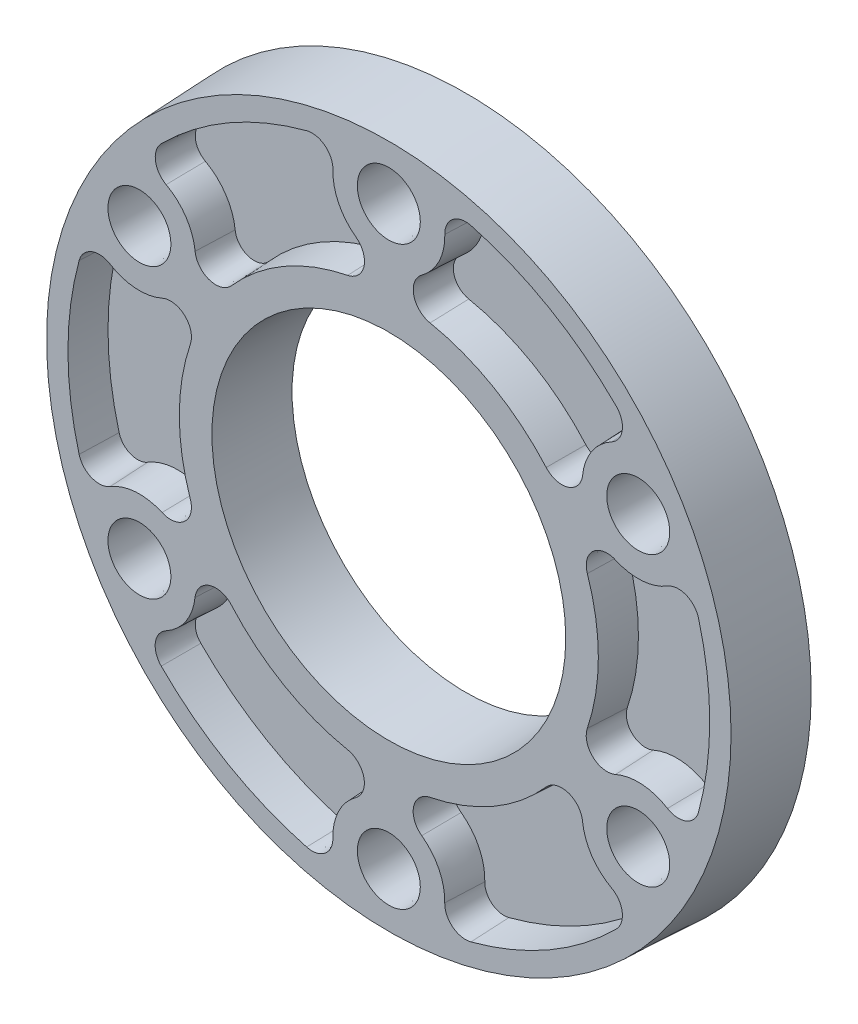
SolidWorks part; units mm, degrees
material "PUR"
ref_plane "Front Plane" through (0, 0, 0) normal (0, 0, 1) x (1, 0, 0)
ref_plane "Top Plane" through (0, 0, 0) normal (0, 1, 0) x (1, 0, 0)
ref_plane "Right Plane" through (0, 0, 0) normal (1, 0, 0) x (0, 0, -1)
sketch "Sketch1" plane through (0, 0, 0) normal (0, 1, 0) x (1, 0, 0)
  line L0 (28.575, 3.175) -> (0, 3.175)
  line L1 (0, 3.175) -> (0, -3.175)
  line L2 (0, -3.175) -> (28.2978, -3.175)
  line L3 (28.2978, -3.175) -> (28.575, 3.175)
  line L4 (0, 3.175) -> (0, -3.175) construction
revolve "Revolve1" add sketch "Sketch1" angle 360 about L4
sketch "Sketch2" plane through (0, 0, 3.175) normal (0, 0, 1) x (1, 0, 0)
  arc A0 (-18.4123, 15.9751) -> (-16.0184, 12.3998) centre (-20.6222, 11.9062) cw
  arc A1 (-16.0184, 12.3998) -> (-13.0062, 11.4436) centre (-14.3021, 12.5838) ccw
  arc A2 (-13.0062, 11.4436) -> (-3.3997, 16.987) centre (0, 0) cw
  arc A3 (-3.3997, 16.987) -> (-2.7222, 20.0749) centre (-3.7384, 18.6796) ccw
  arc A4 (-2.7222, 20.0749) -> (-4.6223, 23.9343) centre (0, 23.8125) cw
  arc A5 (-4.6223, 23.9343) -> (-6.7895, 25.6484) centre (-6.3478, 23.9797) ccw
  arc A6 (-6.7895, 25.6484) -> (-18.8124, 18.7091) centre (0, 0) ccw
  arc A7 (-18.8124, 18.7091) -> (-18.4123, 15.9751) centre (-17.5885, 17.4919) ccw
extrude "Cut-Extrude1" cut sketch "Sketch2" against normal blind 3.175 draft 2.5
sketch "Sketch3" plane through (0, 0, 3.175) normal (0, 0, 1) x (1, 0, 0)
  arc A0 (4.6287, 23.9331) -> (2.7294, 20.0722) centre (0, 23.8125) cw
  arc A1 (2.7294, 20.0722) -> (3.4074, 16.9855) centre (3.7469, 18.6779) ccw
  arc A2 (3.4074, 16.9855) -> (13.0114, 11.4377) centre (0, 0) cw
  arc A3 (13.0114, 11.4377) -> (16.0242, 12.3949) centre (14.3078, 12.5773) ccw
  arc A4 (16.0242, 12.3949) -> (18.4165, 15.9701) centre (20.6222, 11.9063) cw
  arc A5 (18.4165, 15.9701) -> (18.8174, 18.7041) centre (17.5931, 17.4872) ccw
  arc A6 (18.8174, 18.7041) -> (6.7964, 25.6466) centre (0, 0) ccw
  arc A7 (6.7964, 25.6466) -> (4.6287, 23.9331) centre (6.3542, 23.978) ccw
extrude "Cut-Extrude2" cut sketch "Sketch3" against normal blind 3.175 draft 2.5
sketch "Sketch4" plane through (0, 0, 3.175) normal (0, 0, 1) x (1, 0, 0)
  arc A0 (23.041, 7.958) -> (18.7478, 7.6724) centre (20.6222, 11.9062) cw
  arc A1 (18.7478, 7.6724) -> (16.4135, 5.5419) centre (18.049, 6.0941) ccw
  arc A2 (16.4135, 5.5419) -> (16.411, -5.5493) centre (0, 0) cw
  arc A3 (16.411, -5.5493) -> (18.7464, -7.6799) centre (18.0462, -6.1022) ccw
  arc A4 (18.7464, -7.6799) -> (23.0388, -7.9641) centre (20.6222, -11.9063) cw
  arc A5 (23.0388, -7.9641) -> (25.6069, -6.9443) centre (23.9409, -6.4925) ccw
  arc A6 (25.6069, -6.9443) -> (25.6087, 6.9375) centre (0, 0) ccw
  arc A7 (25.6087, 6.9375) -> (23.041, 7.958) centre (23.9427, 6.4861) ccw
extrude "Cut-Extrude3" cut sketch "Sketch4" against normal blind 3.175 draft 2.5
sketch "Sketch5" plane through (0, 0, 3.175) normal (0, 0, 1) x (1, 0, 0)
  arc A0 (18.4123, -15.9751) -> (16.0184, -12.3998) centre (20.6222, -11.9062) cw
  arc A1 (16.0184, -12.3998) -> (13.0062, -11.4436) centre (14.3021, -12.5838) ccw
  arc A2 (13.0062, -11.4436) -> (3.3997, -16.987) centre (0, 0) cw
  arc A3 (3.3997, -16.987) -> (2.7222, -20.0749) centre (3.7384, -18.6796) ccw
  arc A4 (2.7222, -20.0749) -> (4.6223, -23.9343) centre (0, -23.8125) cw
  arc A5 (4.6223, -23.9343) -> (6.7895, -25.6484) centre (6.3478, -23.9797) ccw
  arc A6 (6.7895, -25.6484) -> (18.8124, -18.7091) centre (0, 0) ccw
  arc A7 (18.8124, -18.7091) -> (18.4123, -15.9751) centre (17.5885, -17.4919) ccw
extrude "Cut-Extrude4" cut sketch "Sketch5" against normal blind 3.175 draft 2.5
sketch "Sketch6" plane through (0, 0, 3.175) normal (0, 0, 1) x (1, 0, 0)
  arc A0 (-4.6287, -23.9331) -> (-2.7294, -20.0722) centre (0, -23.8125) cw
  arc A1 (-2.7294, -20.0722) -> (-3.4074, -16.9855) centre (-3.7469, -18.6779) ccw
  arc A2 (-3.4074, -16.9855) -> (-13.0114, -11.4377) centre (0, 0) cw
  arc A3 (-13.0114, -11.4377) -> (-16.0242, -12.3949) centre (-14.3078, -12.5773) ccw
  arc A4 (-16.0242, -12.3949) -> (-18.4165, -15.9701) centre (-20.6222, -11.9062) cw
  arc A5 (-18.4165, -15.9701) -> (-18.8174, -18.7041) centre (-17.5931, -17.4872) ccw
  arc A6 (-18.8174, -18.7041) -> (-6.7964, -25.6466) centre (0, 0) ccw
  arc A7 (-6.7964, -25.6466) -> (-4.6287, -23.9331) centre (-6.3542, -23.978) ccw
extrude "Cut-Extrude5" cut sketch "Sketch6" against normal blind 3.175 draft 2.5
sketch "Sketch7" plane through (0, 0, 3.175) normal (0, 0, 1) x (1, 0, 0)
  arc A0 (-23.041, -7.958) -> (-18.7478, -7.6724) centre (-20.6222, -11.9062) cw
  arc A1 (-18.7478, -7.6724) -> (-16.4135, -5.5419) centre (-18.049, -6.0941) ccw
  arc A2 (-16.4135, -5.5419) -> (-16.411, 5.5493) centre (0, 0) cw
  arc A3 (-16.411, 5.5493) -> (-18.7464, 7.6799) centre (-18.0462, 6.1022) ccw
  arc A4 (-18.7464, 7.6799) -> (-23.0388, 7.9641) centre (-20.6222, 11.9063) cw
  arc A5 (-23.0388, 7.9641) -> (-25.6069, 6.9443) centre (-23.9409, 6.4925) ccw
  arc A6 (-25.6069, 6.9443) -> (-25.6087, -6.9375) centre (0, 0) ccw
  arc A7 (-25.6087, -6.9375) -> (-23.041, -7.958) centre (-23.9427, -6.4861) ccw
extrude "Cut-Extrude6" cut sketch "Sketch7" against normal blind 3.175 draft 2.5
hole_wizard "Hole1" positions "Sketch9" profile "Sketch8" legacy
sketch "Sketch9" plane through (0, 0, 3.175) normal (0, 0, 1) x (1, 0, 0)
  point P0 (0, 23.8125)
sketch "Sketch8" plane through (0, 23.8125, 3.175) normal (1, 0, 0) x (0, -1, 0)
  line L0 (0, 0) -> (0, 6.35)
  line L1 (0, 6.35) -> (2.3818, 6.35)
  line L2 (2.3818, 6.35) -> (2.6035, 0)
  line L3 (2.6035, 0) -> (0, 0)
  line L4 (0, 110) -> (0, -10) construction
  dimension "Minor Diameter" = 4.7635
  dimension "Depth" = 6.35
  dimension "Major Diameter" = 5.207
hole_wizard "Hole2" positions "Sketch11" profile "Sketch10" legacy
sketch "Sketch11" plane through (0, 0, 3.175) normal (0, 0, 1) x (1, 0, 0)
  point P0 (-20.6222, -11.9062)
sketch "Sketch10" plane through (-20.6222, -11.9062, 3.175) normal (1, 0, 0) x (0, -1, 0)
  line L0 (0, 0) -> (0, 6.35)
  line L1 (0, 6.35) -> (2.3263, 6.35)
  line L2 (2.3263, 6.35) -> (2.6035, 0)
  line L3 (2.6035, 0) -> (0, 0)
  line L4 (0, 110) -> (0, -10) construction
  dimension "Minor Diameter" = 4.6525
  dimension "Depth" = 6.35
  dimension "Major Diameter" = 5.207
hole_wizard "Hole3" positions "Sketch13" profile "Sketch12" legacy
sketch "Sketch13" plane through (0, 0, 3.175) normal (0, 0, 1) x (1, 0, 0)
  point P0 (0, -23.8125)
sketch "Sketch12" plane through (0, -23.8125, 3.175) normal (1, 0, 0) x (0, -1, 0)
  line L0 (0, 0) -> (0, 6.35)
  line L1 (0, 6.35) -> (2.3263, 6.35)
  line L2 (2.3263, 6.35) -> (2.6035, 0)
  line L3 (2.6035, 0) -> (0, 0)
  line L4 (0, 110) -> (0, -10) construction
  dimension "Minor Diameter" = 4.6525
  dimension "Depth" = 6.35
  dimension "Major Diameter" = 5.207
hole_wizard "Hole4" positions "Sketch15" profile "Sketch14" legacy
sketch "Sketch15" plane through (0, 0, 3.175) normal (0, 0, 1) x (1, 0, 0)
  point P0 (20.6222, -11.9062)
sketch "Sketch14" plane through (20.6222, -11.9062, 3.175) normal (1, 0, 0) x (0, -1, 0)
  line L0 (0, 0) -> (0, 6.35)
  line L1 (0, 6.35) -> (2.3263, 6.35)
  line L2 (2.3263, 6.35) -> (2.6035, 0)
  line L3 (2.6035, 0) -> (0, 0)
  line L4 (0, 110) -> (0, -10) construction
  dimension "Minor Diameter" = 4.6525
  dimension "Depth" = 6.35
  dimension "Major Diameter" = 5.207
hole_wizard "Hole5" positions "Sketch17" profile "Sketch16" legacy
sketch "Sketch17" plane through (0, 0, 3.175) normal (0, 0, 1) x (1, 0, 0)
  point P0 (20.6222, 11.9062)
sketch "Sketch16" plane through (20.6222, 11.9062, 3.175) normal (1, 0, 0) x (0, -1, 0)
  line L0 (0, 0) -> (0, 6.35)
  line L1 (0, 6.35) -> (2.3263, 6.35)
  line L2 (2.3263, 6.35) -> (2.6035, 0)
  line L3 (2.6035, 0) -> (0, 0)
  line L4 (0, 110) -> (0, -10) construction
  dimension "Minor Diameter" = 4.6525
  dimension "Depth" = 6.35
  dimension "Major Diameter" = 5.207
hole_wizard "Hole6" positions "Sketch19" profile "Sketch18" legacy
sketch "Sketch19" plane through (0, 0, 3.175) normal (0, 0, 1) x (1, 0, 0)
  point P0 (0, 0)
sketch "Sketch18" plane through (0, 0, 3.175) normal (1, 0, 0) x (0, -1, 0)
  line L0 (0, 0) -> (0, 6.35)
  line L1 (0, 6.35) -> (14.351, 6.35)
  line L2 (14.351, 6.35) -> (14.6282, 0)
  line L3 (14.6282, 0) -> (0, 0)
  line L4 (0, 110) -> (0, -10) construction
  dimension "Minor Diameter" = 28.702
  dimension "Depth" = 6.35
  dimension "Major Diameter" = 29.2565
hole_wizard "Hole7" positions "Sketch21" profile "Sketch20" legacy
sketch "Sketch21" plane through (0, 0, 3.175) normal (0, 0, 1) x (1, 0, 0)
  point P0 (-20.6222, 11.9062)
sketch "Sketch20" plane through (-20.6222, 11.9062, 3.175) normal (1, 0, 0) x (0, -1, 0)
  line L0 (0, 0) -> (0, 6.35)
  line L1 (0, 6.35) -> (2.3818, 6.35)
  line L2 (2.3818, 6.35) -> (2.6035, 0)
  line L3 (2.6035, 0) -> (0, 0)
  line L4 (0, 110) -> (0, -10) construction
  dimension "Minor Diameter" = 4.7635
  dimension "Depth" = 6.35
  dimension "Major Diameter" = 5.207
